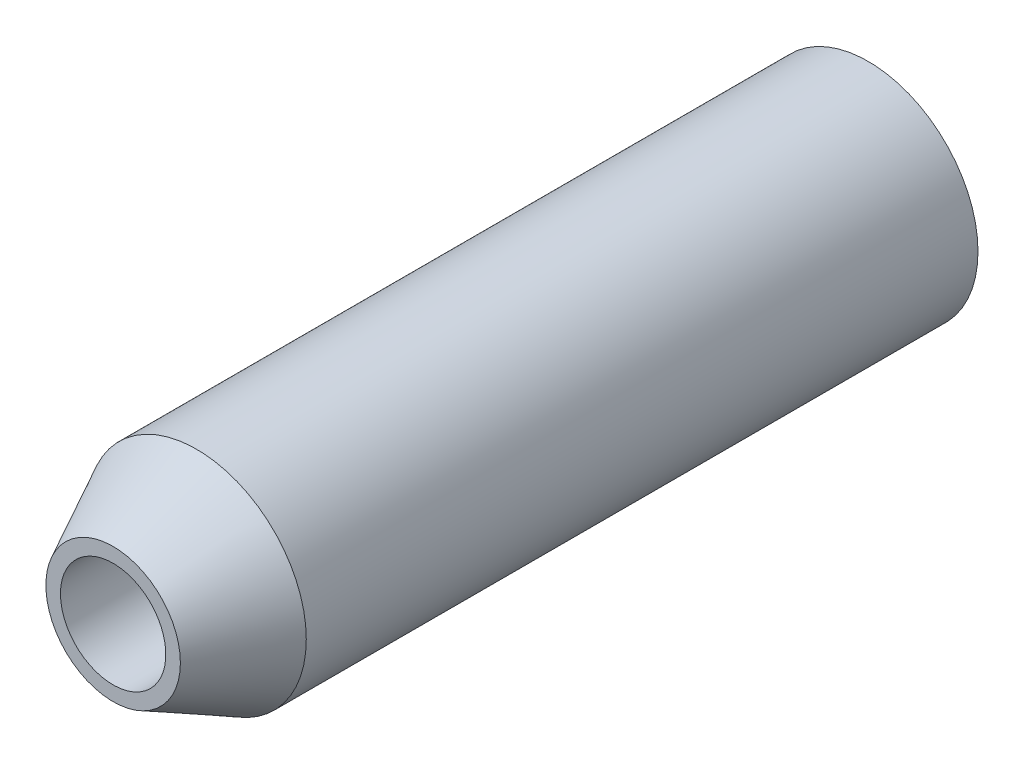
SolidWorks part; units mm, degrees
material "O1 Steel"
ref_plane "Alzado" through (0, 0, 0) normal (0, 0, 1) x (1, 0, 0)
ref_plane "Planta" through (0, 0, 0) normal (0, 1, 0) x (1, 0, 0)
ref_plane "Vista lateral" through (0, 0, 0) normal (1, 0, 0) x (0, 0, -1)
sketch "Croquis3" plane through (0, 0, 0) normal (0, 0, 1) x (1, 0, 0)
  circle A0 centre (0, 0) radius 3.175
  dimension "D1" = 6.35
extrude "Saliente-Extruir2" add sketch "Croquis3" along normal mid plane 21.844
sketch "Croquis5" plane through (0, 0, -10.922) normal (0, 0, -1) x (-1, 0, 0)
  point P0 (0, 0)
hole_wizard "Refrentado para tornillo con cabeza hueca de 1/41" positions "Croquis5" profile "Croquis6" counterbore size "1/4" standard "Ansi Inch" end condition through all
sketch "Croquis6" plane through (0, 0, -10.922) normal (1, 0, 0) x (0, 1, 0)
  line L0 (0, 0) -> (0, 21.844)
  line L1 (0, 21.844) -> (1.524, 21.844)
  line L3 (1.524, 21.844) -> (1.524, 17.145)
  line L4 (1.524, 17.145) -> (2.3495, 17.145)
  line L5 (2.3495, 17.145) -> (2.3495, 0)
  line L7 (2.3495, 0) -> (0, 0)
  line L11 (0, -6.35) -> (0, 107.95) construction
  dimension "Diámetro de taladro hasta el siguiente" = 3.048
  dimension "Profundidad de taladro hasta el siguiente" = 21.844
  dimension "Diámetro de refrentado" = 4.699
  dimension "Profundidad de refrentado" = 17.145
chamfer "Chaflán1" distance 2.413 angle 27 1 edges at (3.175, 0, 10.922)
